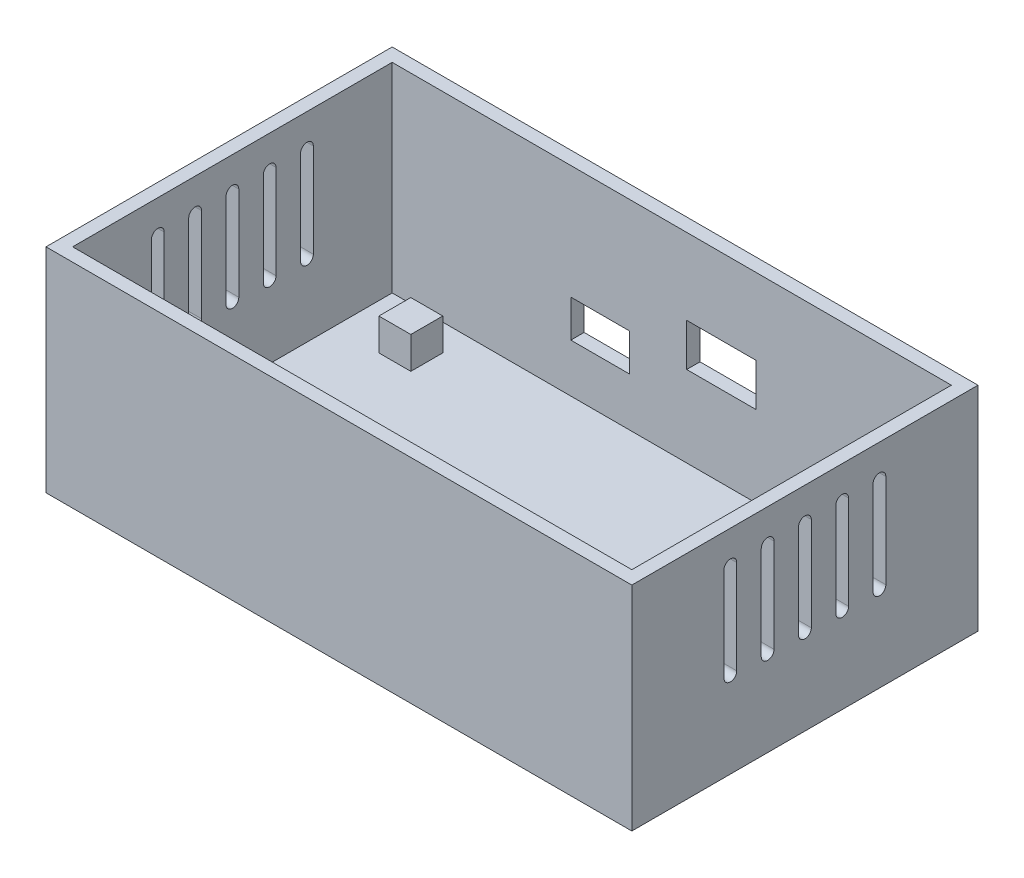
SolidWorks part; units mm, degrees
ref_plane "Front Plane" through (0, 0, 0) normal (0, 0, 1) x (1, 0, 0)
ref_plane "Top Plane" through (0, 0, 0) normal (0, 1, 0) x (1, 0, 0)
ref_plane "Right Plane" through (0, 0, 0) normal (1, 0, 0) x (0, 0, -1)
sketch "Croquis_contorno" plane through (0, 0, 0) normal (0, 1, 0) x (1, 0, 0)
  line L1 (-55, -32.5) -> (55, -32.5)
  line L2 (-55, -32.5) -> (-55, 32.5)
  line L3 (-55, 32.5) -> (55, 32.5)
  line L4 (55, -32.5) -> (55, 32.5)
  line L5 (-55, -32.5) -> (55, 32.5) construction
  line L6 (-55, 32.5) -> (55, -32.5) construction
  point P0 (0, 0)
  dimension "D1" = 110
  dimension "D2" = 65
extrude "Cuerpo" add sketch "Croquis_contorno" along normal blind 40
ref_plane "Plano_Top Plane_+40" through (0, 40, 0) normal (0, 1, 0) x (1, 0, 0)
sketch "Croquis_vaciado" plane through (0, 40, 0) normal (0, 1, 0) x (1, 0, 0)
  line L1 (-52.5, -30) -> (52.5, -30)
  line L2 (-52.5, -30) -> (-52.5, 30)
  line L3 (-52.5, 30) -> (52.5, 30)
  line L4 (52.5, -30) -> (52.5, 30)
  line L5 (-52.5, -30) -> (52.5, 30) construction
  line L6 (-52.5, 30) -> (52.5, -30) construction
  dimension "D1" = 105
  dimension "D2" = 60
extrude "Vaciado" cut sketch "Croquis_vaciado" against normal blind 37.5
ref_plane "Plano_Top Plane_+2_5" through (0, 2.5, 0) normal (0, 1, 0) x (1, 0, 0)
sketch "Croquis_apoyos_pcb" plane through (0, 2.5, 0) normal (0, 1, 0) x (1, 0, 0)
  line L1 (-44, 19) -> (-38, 19)
  line L2 (-44, 19) -> (-44, 25)
  line L3 (-44, 25) -> (-38, 25)
  line L4 (-38, 19) -> (-38, 25)
  line L5 (-44, 19) -> (-38, 25) construction
  line L6 (-44, 25) -> (-38, 19) construction
  line L7 (-44, -25) -> (-38, -25)
  line L8 (-44, -25) -> (-44, -19)
  line L9 (-44, -19) -> (-38, -19)
  line L10 (-38, -25) -> (-38, -19)
  line L11 (-44, -25) -> (-38, -19) construction
  line L12 (-44, -19) -> (-38, -25) construction
  line L13 (38, 19) -> (44, 19)
  line L14 (38, 19) -> (38, 25)
  line L15 (38, 25) -> (44, 25)
  line L16 (44, 19) -> (44, 25)
  line L17 (38, 19) -> (44, 25) construction
  line L18 (38, 25) -> (44, 19) construction
  line L19 (38, -25) -> (44, -25)
  line L20 (38, -25) -> (38, -19)
  line L21 (38, -19) -> (44, -19)
  line L22 (44, -25) -> (44, -19)
  line L23 (38, -25) -> (44, -19) construction
  line L24 (38, -19) -> (44, -25) construction
  point P0 (-41, -22)
  point P9 (41, 22)
  point P14 (41, -22)
  dimension "D1" = 6
  dimension "D2" = 6
extrude "Apoyos_PCB" add sketch "Croquis_apoyos_pcb" along normal blind 6
sketch "Croquis_salidas" plane through (0, 0, 0) normal (0, 0, 1) x (1, 0, 0)
  line L1 (2.8, 17.7) -> (15.8, 17.7)
  line L2 (2.8, 17.7) -> (2.8, 25.7)
  line L3 (2.8, 25.7) -> (15.8, 25.7)
  line L4 (15.8, 17.7) -> (15.8, 25.7)
  line L5 (2.8, 17.7) -> (15.8, 25.7) construction
  line L6 (2.8, 25.7) -> (15.8, 17.7) construction
  line L7 (-18.96, 11.6) -> (-7.96, 11.6)
  line L8 (-18.96, 11.6) -> (-18.96, 18.6)
  line L9 (-18.96, 18.6) -> (-7.96, 18.6)
  line L10 (-7.96, 11.6) -> (-7.96, 18.6)
  line L11 (-18.96, 11.6) -> (-7.96, 18.6) construction
  line L12 (-18.96, 18.6) -> (-7.96, 11.6) construction
  point P0 (-13.46, 15.1)
  dimension "D1" = 13
  dimension "D2" = 8
  dimension "D3" = 11
  dimension "D4" = 7
extrude "Salidas_USB_y_panel" cut sketch "Croquis_salidas" against normal through all
sketch "Croquis_ventilas" plane through (0, 0, 0) normal (1, 0, 0) x (0, 0, -1)
  line L0 (-14, 16.2) -> (-14, 33.8) construction
  line L1 (-15.2, 16.2) -> (-15.2, 33.8)
  line L2 (-12.8, 16.2) -> (-12.8, 33.8)
  line L3 (-7, 16.2) -> (-7, 33.8) construction
  line L4 (-8.2, 16.2) -> (-8.2, 33.8)
  line L5 (-5.8, 16.2) -> (-5.8, 33.8)
  line L6 (0, 16.2) -> (0, 33.8) construction
  line L7 (-1.2, 16.2) -> (-1.2, 33.8)
  line L8 (1.2, 16.2) -> (1.2, 33.8)
  line L9 (7, 16.2) -> (7, 33.8) construction
  line L10 (5.8, 16.2) -> (5.8, 33.8)
  line L11 (8.2, 16.2) -> (8.2, 33.8)
  line L12 (14, 16.2) -> (14, 33.8) construction
  line L13 (12.8, 16.2) -> (12.8, 33.8)
  line L14 (15.2, 16.2) -> (15.2, 33.8)
  arc A0 (-15.2, 16.2) -> (-12.8, 16.2) centre (-14, 16.2) ccw
  arc A1 (-12.8, 33.8) -> (-15.2, 33.8) centre (-14, 33.8) ccw
  arc A2 (-8.2, 16.2) -> (-5.8, 16.2) centre (-7, 16.2) ccw
  arc A3 (-5.8, 33.8) -> (-8.2, 33.8) centre (-7, 33.8) ccw
  arc A4 (-1.2, 16.2) -> (1.2, 16.2) centre (0, 16.2) ccw
  arc A5 (1.2, 33.8) -> (-1.2, 33.8) centre (0, 33.8) ccw
  arc A6 (5.8, 16.2) -> (8.2, 16.2) centre (7, 16.2) ccw
  arc A7 (8.2, 33.8) -> (5.8, 33.8) centre (7, 33.8) ccw
  arc A8 (12.8, 16.2) -> (15.2, 16.2) centre (14, 16.2) ccw
  arc A9 (15.2, 33.8) -> (12.8, 33.8) centre (14, 33.8) ccw
  point P2 (-14, 25)
  point P7 (-7, 25)
  point P14 (0, 25)
  point P22 (7, 25)
  point P29 (14, 25)
  point P36 (0, 0)
extrude "Ventilas_laterales" cut sketch "Croquis_ventilas" along normal through all and the other way through all
sketch "Croquis_tornillos" plane through (0, 0, 0) normal (0, 1, 0) x (1, 0, 0)
  circle A0 centre (-30, 0) radius 1.7
  circle A1 centre (30, 0) radius 1.7
  dimension "D1" = 3.4
extrude "Agujeros_M3" cut sketch "Croquis_tornillos" along normal through all and the other way through all
